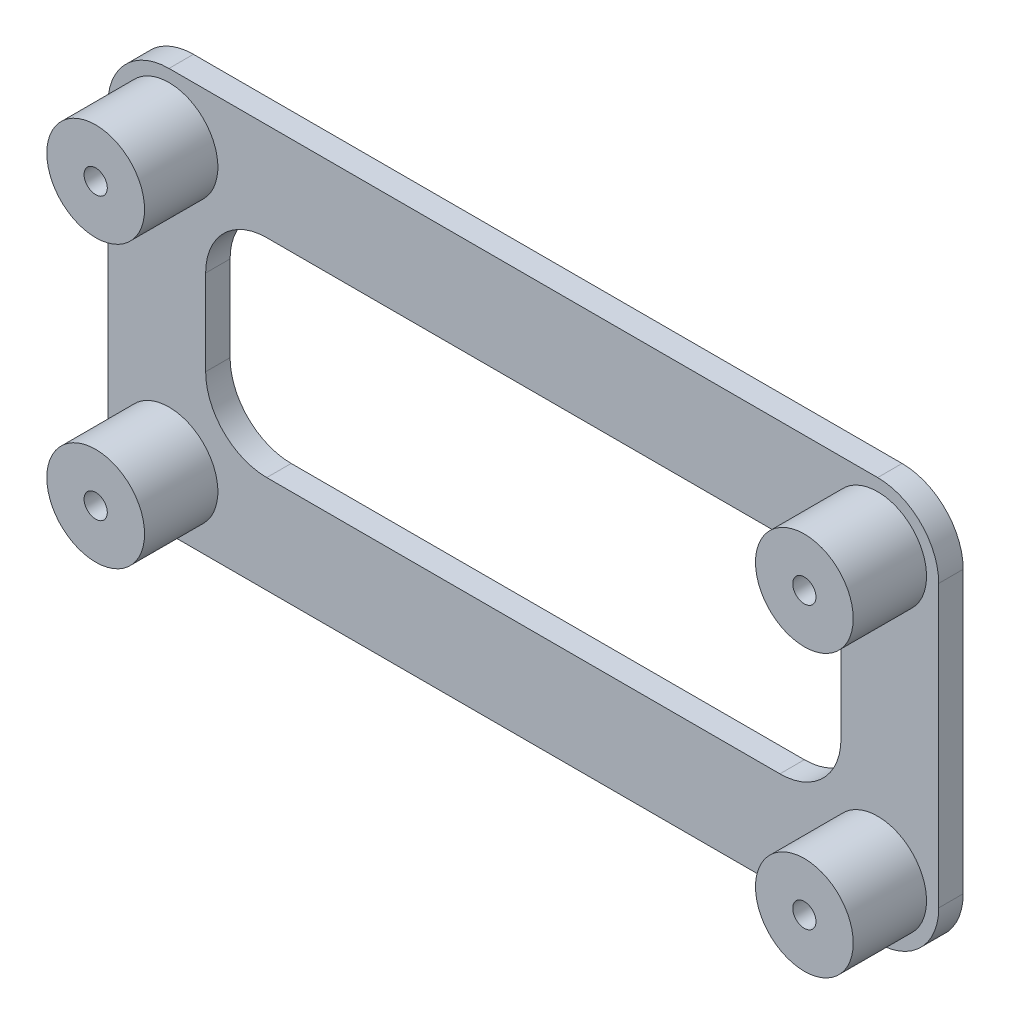
SolidWorks part; units mm, degrees
ref_plane "Front Plane" through (0, 0, 0) normal (0, 0, 1) x (1, 0, 0)
ref_plane "Top Plane" through (0, 0, 0) normal (0, 1, 0) x (1, 0, 0)
ref_plane "Right Plane" through (0, 0, 0) normal (1, 0, 0) x (0, 0, -1)
sketch "Sketch1" plane through (0, 0, 0) normal (0, 0, 1) x (1, 0, 0)
  line L1 (-29, -11.5) -> (29, -11.5) construction
  line L2 (-29, -11.5) -> (-29, 11.5) construction
  line L3 (-29, 11.5) -> (29, 11.5) construction
  line L4 (29, -11.5) -> (29, 11.5) construction
  line L5 (-29, -11.5) -> (29, 11.5) construction
  line L6 (-29, 11.5) -> (29, -11.5) construction
  line L7 (-34, -16.5) -> (34, -16.5)
  line L8 (-34, -16.5) -> (-34, 16.5)
  line L9 (-34, 16.5) -> (34, 16.5)
  line L10 (34, -16.5) -> (34, 16.5)
  line L13 (-26, -8.5) -> (26, -8.5)
  line L14 (-26, -8.5) -> (-26, 8.5)
  line L15 (-26, 8.5) -> (26, 8.5)
  line L16 (26, -8.5) -> (26, 8.5)
  line L17 (-26, -8.5) -> (26, 8.5) construction
  line L18 (-26, 8.5) -> (26, -8.5) construction
  circle A0 centre (-29, 11.5) radius 0.95
  circle A1 centre (29, 11.5) radius 0.95
  circle A2 centre (29, -11.5) radius 0.95
  circle A3 centre (-29, -11.5) radius 0.95
  point P0 (0, 0)
  point P6 (0, 0)
  point P11 (0, 0)
  dimension "D6" = 1.9
  dimension "D1" = 58
  dimension "D2" = 23
  dimension "D3" = 5
  dimension "D4" = 5
  dimension "D5" = 3
  dimension "D7" = 3
extrude "Boss-Extrude1" add sketch "Sketch1" along normal blind 2
sketch "Sketch2" plane through (0, 0, 2) normal (0, 0, 1) x (1, 0, 0)
  circle A0 centre (-29, 11.5) radius 4
  circle A1 centre (29, 11.5) radius 4
  circle A2 centre (29, -11.5) radius 4
  circle A3 centre (-29, -11.5) radius 4
  circle A4 centre (-29, -11.5) radius 0.95 construction
  circle A5 centre (29, -11.5) radius 0.95 construction
  circle A6 centre (29, 11.5) radius 0.95 construction
  circle A7 centre (-29, 11.5) radius 0.95 construction
  circle A8 centre (-29, -11.5) radius 0.95
  circle A9 centre (29, -11.5) radius 0.95
  circle A10 centre (29, 11.5) radius 0.95
  circle A11 centre (-29, 11.5) radius 0.95
  dimension "D1" = 8
extrude "Boss-Extrude2" add sketch "Sketch2" along normal blind 6
fillet "Fillet1" radius 5 8 edges at (26, -8.5, 1) (26, 8.5, 1) (-26, 8.5, 1) (-34, 16.5, 1) (34, 16.5, 1) (34, -16.5, 1) (-34, -16.5, 1) (-26, -8.5, 1)
